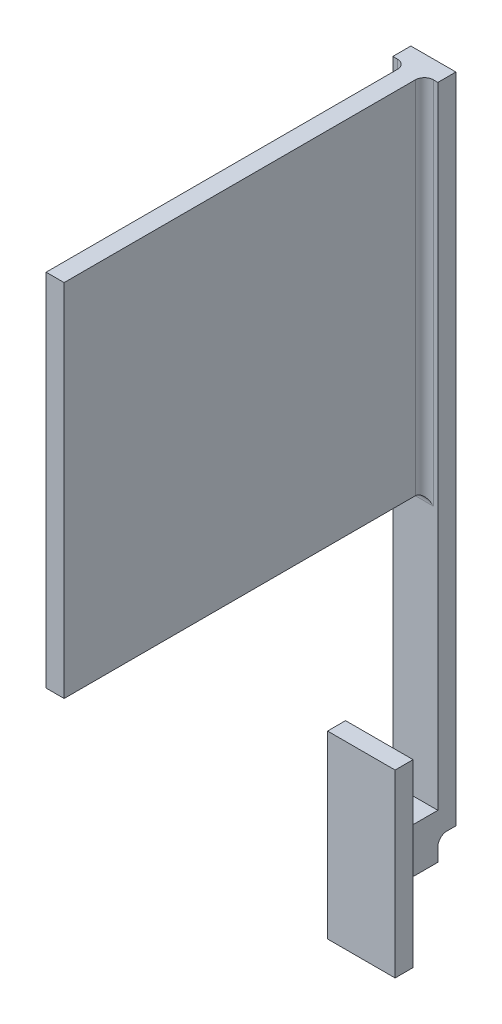
SolidWorks part; units mm, degrees
ref_plane "Front Plane" through (0, 0, 0) normal (0, 0, 1) x (1, 0, 0)
ref_plane "Top Plane" through (0, 0, 0) normal (0, 1, 0) x (1, 0, 0)
ref_plane "Right Plane" through (0, 0, 0) normal (1, 0, 0) x (0, 0, -1)
sketch "Sketch1" plane through (0, 0, 0) normal (0, 0, 1) x (1, 0, 0)
  line L1 (-3.75, -10) -> (3.75, -10)
  line L2 (-3.75, -10) -> (-3.75, 10)
  line L3 (-3.75, 10) -> (3.75, 10)
  line L4 (3.75, -10) -> (3.75, 10)
  line L5 (-3.75, -10) -> (3.75, 10) construction
  line L6 (-3.75, 10) -> (3.75, -10) construction
  point P0 (0, 0)
  dimension "D1" = 20
  dimension "D2" = 7.5
extrude "Boss-Extrude1" add sketch "Sketch1" along normal blind 2
sketch "Sketch2" plane through (0, 0, 0) normal (0, 0, -1) x (-1, 0, 0)
  line L1 (2.5, -2.5) -> (-2.5, -2.5)
  line L2 (2.5, -2.5) -> (2.5, 2.5)
  line L3 (2.5, 2.5) -> (-2.5, 2.5)
  line L4 (-2.5, -2.5) -> (-2.5, 2.5)
  line L5 (2.5, -2.5) -> (-2.5, 2.5) construction
  line L6 (2.5, 2.5) -> (-2.5, -2.5) construction
  point P0 (0, 0)
  dimension "D1" = 5
  dimension "D2" = 5
extrude "Boss-Extrude2" add sketch "Sketch2" along normal blind 4
sketch "Sketch3" plane through (0, 0, -4) normal (0, 0, -1) x (-1, 0, 0)
  line L1 (-2.5, 0) -> (2.5, 0)
  line L2 (-2.5, 0) -> (-2.5, 72.5)
  line L3 (-2.5, 72.5) -> (2.5, 72.5)
  line L4 (2.5, 0) -> (2.5, 72.5)
  line L5 (-2.5, 2.5) -> (-2.5, -2.5) construction
  point P4 (0, 0)
  dimension "D1" = 72.5
extrude "Boss-Extrude3" add sketch "Sketch3" along normal blind 2
sketch "Sketch4" plane through (0, 0, -4) normal (0, 0, 1) x (1, 0, 0)
  line L0 (-2.5, 72.5) -> (2.5, 72.5) construction
  line L1 (-1, 72.5) -> (1, 72.5)
  line L2 (-1, 72.5) -> (-1, 32.5)
  line L3 (-1, 32.5) -> (1, 32.5)
  line L4 (1, 72.5) -> (1, 32.5)
  point P10 (0, 72.5)
  dimension "D1" = 2
  dimension "D2" = 40
extrude "Boss-Extrude4" add sketch "Sketch4" along normal blind 40
fillet "Fillet1" radius 1 1 edges at (0, 0, -4)
fillet "Fillet2" radius 1 3 edges at (-1, 52.5, -4) (1, 52.5, -4) (0, 32.5, -4)
